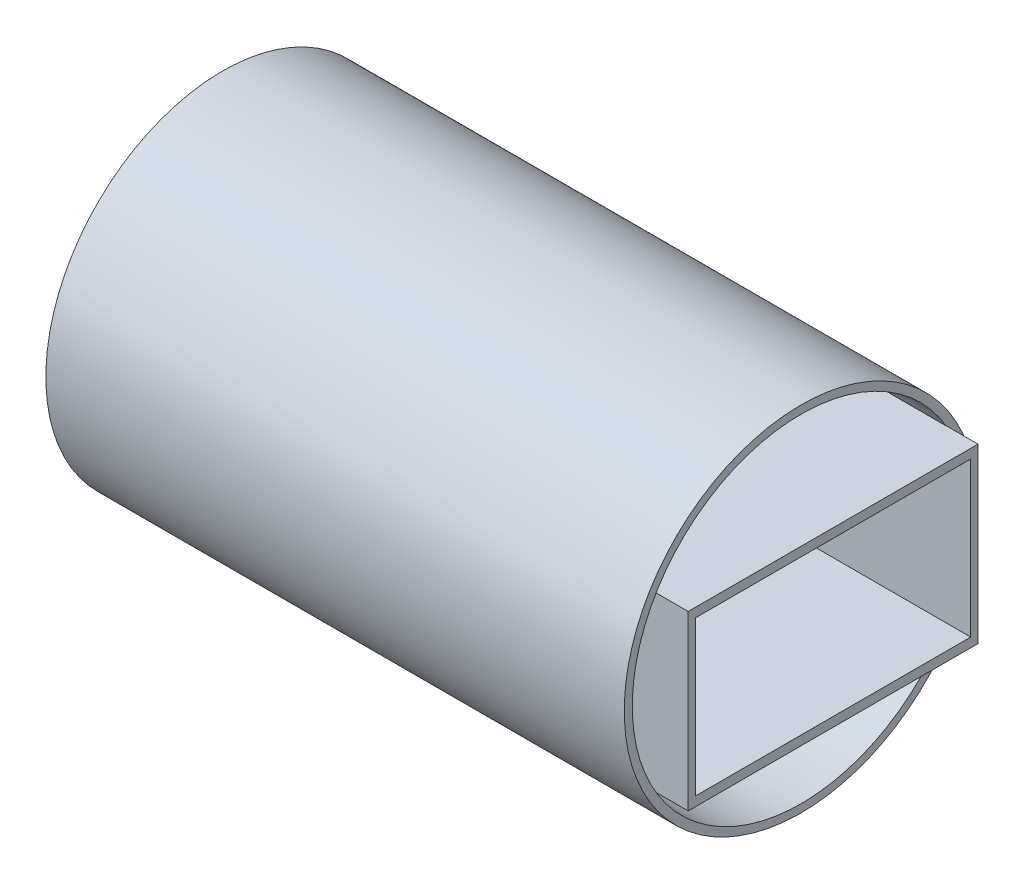
SolidWorks part; units mm, degrees
ref_plane "Front Plane" through (0, 0, 0) normal (0, 0, 1) x (1, 0, 0)
ref_plane "Top Plane" through (0, 0, 0) normal (0, 1, 0) x (1, 0, 0)
ref_plane "Right Plane" through (0, 0, 0) normal (1, 0, 0) x (0, 0, -1)
sketch "Sketch1" plane through (0, 0, 0) normal (1, 0, 0) x (0, 0, -1)
  circle A0 centre (0, 0) radius 139.7
  circle A1 centre (0, 0) radius 133.35
extrude "Boss-Extrude1" add sketch "Sketch1" along normal blind 457.2
sketch "Sketch2" plane through (0, 0, 0) normal (-1, 0, 0) x (0, 0, 1)
  line L0 (-102.1418, -60.9055) -> (-114.534, -68.2948) construction
  line L1 (114.534, 68.2948) -> (-114.534, 68.2948)
  line L2 (114.534, 68.2948) -> (114.534, -68.2948)
  line L3 (114.534, -68.2948) -> (-114.534, -68.2948)
  line L4 (-114.534, 68.2948) -> (-114.534, -68.2948)
  line L5 (114.534, 68.2948) -> (102.3246, 61.0145) construction
  line L6 (114.534, -68.2948) -> (102.1418, -60.9055) construction
  line L7 (108.7461, 61.0145) -> (-108.7461, 61.0145)
  line L8 (108.7461, 61.0145) -> (108.7461, -60.9055)
  line L9 (108.7461, -60.9055) -> (-108.7461, -60.9055)
  line L10 (-108.7461, 61.0145) -> (-108.7461, -60.9055)
  line L13 (-102.3246, 61.0145) -> (-114.534, 68.2948) construction
  circle A0 centre (0, 0) radius 133.35 construction
  point P0 (0, 0)
  point P8 (0, 0)
extrude "Boss-Extrude2" add sketch "Sketch2" against normal blind 482.6 separate body
sketch "Sketch3" plane through (0, 68.2948, 0) normal (0, 1, 0) x (1, 0, 0)
  line L5 (320.5989, -114.155) -> (282.4989, -114.155)
  line L6 (320.5989, -114.155) -> (320.5989, -152.255)
  line L7 (320.5989, -152.255) -> (282.4989, -152.255)
  line L8 (282.4989, -114.155) -> (282.4989, -152.255)
  line L9 (320.5989, -114.155) -> (282.4989, -152.255) construction
  line L10 (320.5989, -152.255) -> (282.4989, -114.155) construction
  point P0 (301.5489, -133.205)
  dimension "D1" = 38.1
  dimension "D2" = 38.1
extrude "Cut-Extrude1" [suppressed] cut sketch "Sketch3" against normal blind 18.542
sketch "Sketch4" plane through (0, -68.2948, 0) normal (0, -1, 0) x (1, 0, 0)
  line L1 (389.5472, -30.335) -> (427.6472, -30.335)
  line L2 (389.5472, -30.335) -> (389.5472, 7.765)
  line L3 (389.5472, 7.765) -> (427.6472, 7.765)
  line L4 (427.6472, -30.335) -> (427.6472, 7.765)
  line L5 (389.5472, -30.335) -> (427.6472, 7.765) construction
  line L6 (389.5472, 7.765) -> (427.6472, -30.335) construction
  point P0 (408.5972, -11.285)
  dimension "D1" = 38.1
  dimension "D2" = 38.1
extrude "Boss-Extrude3" [suppressed] add sketch "Sketch4" against normal blind 13.97
sketch "Sketch5" plane through (0, -68.2948, 0) normal (0, -1, 0) x (-1, 0, 0)
  line L1 (-8.9789, -197.6016) -> (-206.6036, -197.6016)
  line L2 (-8.9789, -197.6016) -> (-8.9789, 17.6871)
  line L3 (-8.9789, 17.6871) -> (-206.6036, 17.6871)
  line L4 (-206.6036, -197.6016) -> (-206.6036, 17.6871)
extrude "Cut-Extrude2" [suppressed] cut sketch "Sketch5" against normal blind 343.916
